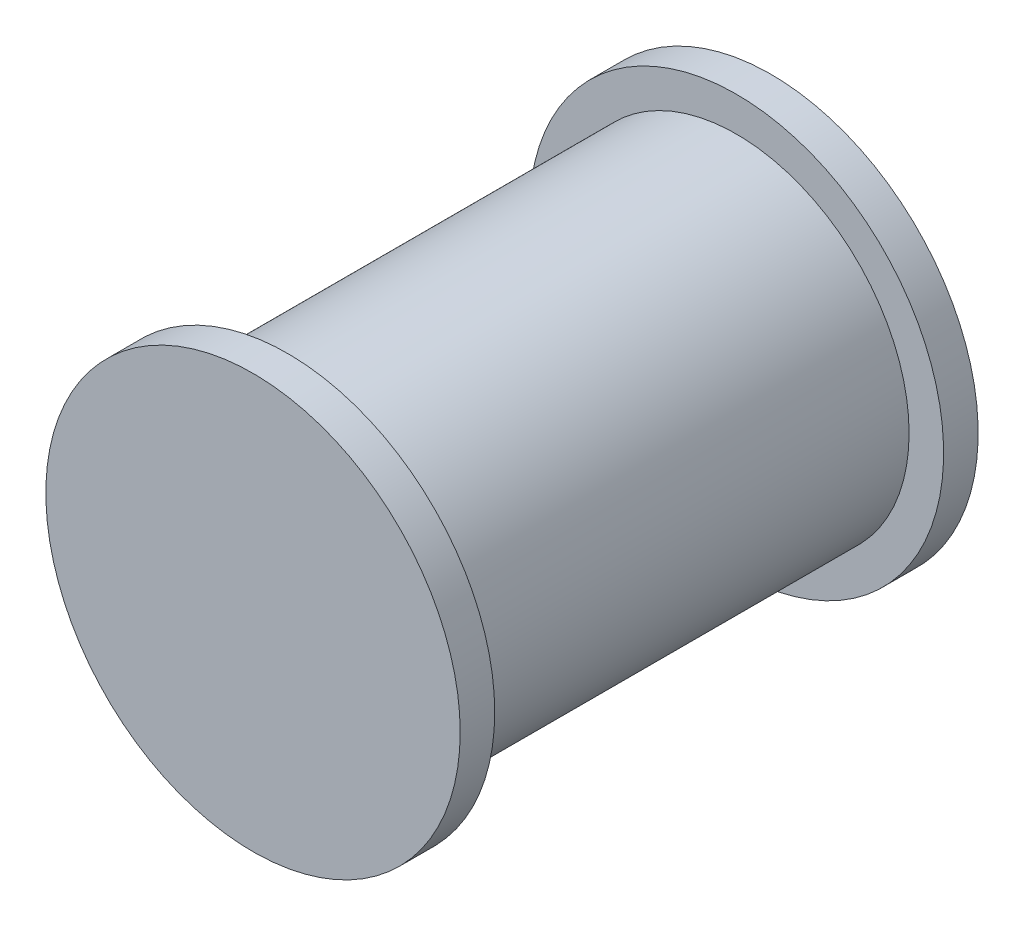
SolidWorks part; units mm, degrees
ref_plane "前视基准面" through (0, 0, 0) normal (0, 0, 1) x (1, 0, 0)
ref_plane "上视基准面" through (0, 0, 0) normal (0, 1, 0) x (1, 0, 0)
ref_plane "右视基准面" through (0, 0, 0) normal (1, 0, 0) x (0, 0, -1)
sketch "草图1" plane through (0, 0, 0) normal (0, 0, 1) x (1, 0, 0)
  circle A0 centre (0, 0) radius 10
extrude "凸台-拉伸1" add sketch "草图1" along normal blind 30
sketch "草图2" plane through (0, 0, 30) normal (0, 0, 1) x (1, 0, 0)
  circle A1 centre (0, 0) radius 10
  circle A2 centre (0, 0) radius 10
  dimension "D1" = 0
extrude "拉伸-薄壁1" add sketch "草图2" against normal blind 2 thin
sketch "草图3" plane through (0, 0, 0) normal (0, 0, -1) x (-1, 0, 0)
  circle A1 centre (0, 0) radius 10
  circle A2 centre (0, 0) radius 10
  dimension "D1" = 0
extrude "拉伸-薄壁2" add sketch "草图3" against normal blind 2 thin
